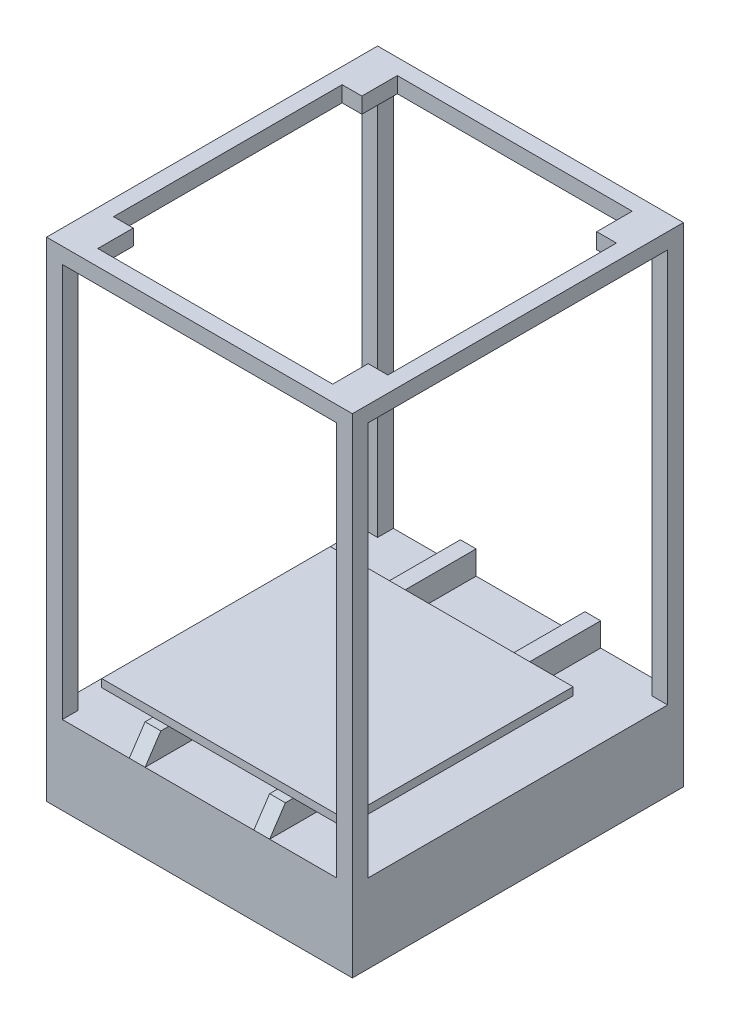
SolidWorks part; units mm, degrees
ref_plane "前视基准面" through (0, 0, 0) normal (0, 0, 1) x (1, 0, 0)
ref_plane "上视基准面" through (0, 0, 0) normal (0, 1, 0) x (1, 0, 0)
ref_plane "右视基准面" through (0, 0, 0) normal (1, 0, 0) x (0, 0, -1)
sketch "草图1" plane through (0, 0, 0) normal (0, 0, 1) x (1, 0, 0)
  line L1 (0, 0) -> (388, 0)
  line L2 (0, 0) -> (0, 100)
  line L3 (0, 100) -> (388, 100)
  line L4 (388, 0) -> (388, 100)
  dimension "D1" = 100
  dimension "D2" = 388
extrude "凸台-拉伸1" add sketch "草图1" against normal blind 420
sketch "草图2" plane through (0, 100, 0) normal (0, 1, 0) x (1, 0, 0)
  line L0 (194, 420) -> (194, -59.7909) construction
  line L1 (388, 420) -> (0, 420) construction
  line L2 (125, 0) -> (125, 420)
  line L3 (388, 0) -> (0, 0) construction
  line L4 (125, 420) -> (105, 420)
  line L5 (105, 420) -> (105, 0)
  line L6 (105, 0) -> (125, 0)
  line L7 (283, 420) -> (283, 0)
  line L8 (263, 420) -> (283, 420)
  line L9 (263, 0) -> (263, 420)
  line L10 (283, 0) -> (263, 0)
  dimension "D1" = 125
  dimension "D2" = 20
extrude "凸台-拉伸2" add sketch "草图2" along normal blind 30
sketch "草图3" plane through (0, 100, 0) normal (0, 1, 0) x (1, 0, 0)
  line L0 (194, 420) -> (194, -6.8216) construction
  line L1 (0, 0) -> (20, 0)
  line L2 (0, 0) -> (0, 20)
  line L3 (0, 20) -> (20, 20)
  line L4 (20, 0) -> (20, 20)
  line L5 (263, 420) -> (125, 420) construction
  line L6 (0, 210) -> (388, 210) construction
  line L7 (0, 420) -> (0, 0) construction
  line L8 (388, 420) -> (388, 0) construction
  line L9 (0, 400) -> (20, 400)
  line L10 (20, 420) -> (20, 400)
  line L11 (0, 420) -> (20, 420)
  line L12 (0, 420) -> (0, 400)
  line L13 (388, 20) -> (368, 20)
  line L14 (368, 0) -> (368, 20)
  line L15 (388, 0) -> (368, 0)
  line L16 (388, 0) -> (388, 20)
  line L17 (388, 420) -> (388, 400)
  line L18 (388, 420) -> (368, 420)
  line L19 (368, 420) -> (368, 400)
  line L20 (388, 400) -> (368, 400)
  dimension "D1" = 20
  dimension "D2" = 20
extrude "凸台-拉伸3" add sketch "草图3" along normal blind 500
sketch "草图4" plane through (0, 600, 0) normal (0, 1, 0) x (1, 0, 0)
  line L1 (0, 0) -> (388, 0)
  line L2 (0, 0) -> (0, 420)
  line L3 (0, 420) -> (388, 420)
  line L4 (388, 0) -> (388, 420)
extrude "凸台-拉伸4" add sketch "草图4" along normal blind 20
sketch "草图6" plane through (0, 130, 0) normal (0, 1, 0) x (1, 0, 0)
  line L0 (388, 420) -> (0, 420) construction
  line L1 (40, 320) -> (348, 320)
  line L2 (40, 320) -> (40, 30)
  line L3 (40, 30) -> (348, 30)
  line L4 (348, 320) -> (348, 30)
  dimension "D1" = 40
  dimension "D2" = 40
  dimension "D3" = 30
  dimension "D4" = 100
extrude "凸台-拉伸6" add sketch "草图6" along normal blind 10
sketch "草图7" plane through (105, 0, 0) normal (-1, 0, 0) x (0, 0, 1)
  line L1 (-20, 600) -> (-20, 100) construction
  line L2 (-30, 130) -> (0, 130) construction
  line L5 (0, 100) -> (-20, 130)
  line L6 (-20, 130) -> (0, 130)
  line L7 (0, 130) -> (0, 100)
extrude "切除-拉伸1" cut sketch "草图7" against normal up to surface (178 mm away) up to face at (283, 120, -198.3333)
sketch "草图8" plane through (0, 620, 0) normal (0, 1, 0) x (1, 0, 0)
  line L0 (388, 0) -> (388, 420) construction
  line L1 (20, 400) -> (368, 400)
  line L2 (20, 400) -> (20, 20)
  line L3 (20, 20) -> (368, 20)
  line L4 (368, 400) -> (368, 20)
  line L5 (0, 420) -> (0, 0) construction
  line L6 (0, 0) -> (388, 0) construction
  line L7 (388, 420) -> (0, 420) construction
  dimension "D1" = 20
  dimension "D2" = 20
  dimension "D3" = 20
  dimension "D4" = 20
extrude "切除-拉伸2" cut sketch "草图8" against normal up to next
sketch "草图9" plane through (368, 0, 0) normal (-1, 0, 0) x (0, 0, 1)
  line L0 (-400, 600) -> (-20, 600) construction
  line L1 (-20, 620) -> (-65, 620)
  line L2 (-20, 620) -> (-20, 600)
  line L3 (-20, 600) -> (-65, 600)
  line L4 (-65, 620) -> (-65, 600)
  line L6 (-400, 620) -> (-355, 620)
  line L7 (-400, 620) -> (-400, 600)
  line L8 (-400, 600) -> (-355, 600)
  line L9 (-355, 620) -> (-355, 600)
  dimension "D1" = 45
  dimension "D2" = 45
extrude "凸台-拉伸7" add sketch "草图9" along normal blind 25
sketch "草图10" plane through (20, 0, 0) normal (1, 0, 0) x (0, 0, -1)
  line L0 (400, 620) -> (400, 600) construction
  line L1 (400, 600) -> (355, 600) construction
  line L2 (355, 600) -> (355, 620) construction
  line L3 (355, 620) -> (400, 620) construction
  line L4 (20, 600) -> (20, 620) construction
  line L5 (20, 620) -> (65, 620) construction
  line L6 (65, 620) -> (65, 600) construction
  line L7 (65, 600) -> (20, 600) construction
  line L8 (400, 620) -> (400, 600)
  line L9 (400, 600) -> (355, 600)
  line L10 (355, 600) -> (355, 620)
  line L11 (355, 620) -> (400, 620)
  line L12 (20, 600) -> (20, 620)
  line L13 (20, 620) -> (65, 620)
  line L14 (65, 620) -> (65, 600)
  line L15 (65, 600) -> (20, 600)
extrude "凸台-拉伸8" add sketch "草图10" along normal blind 25
